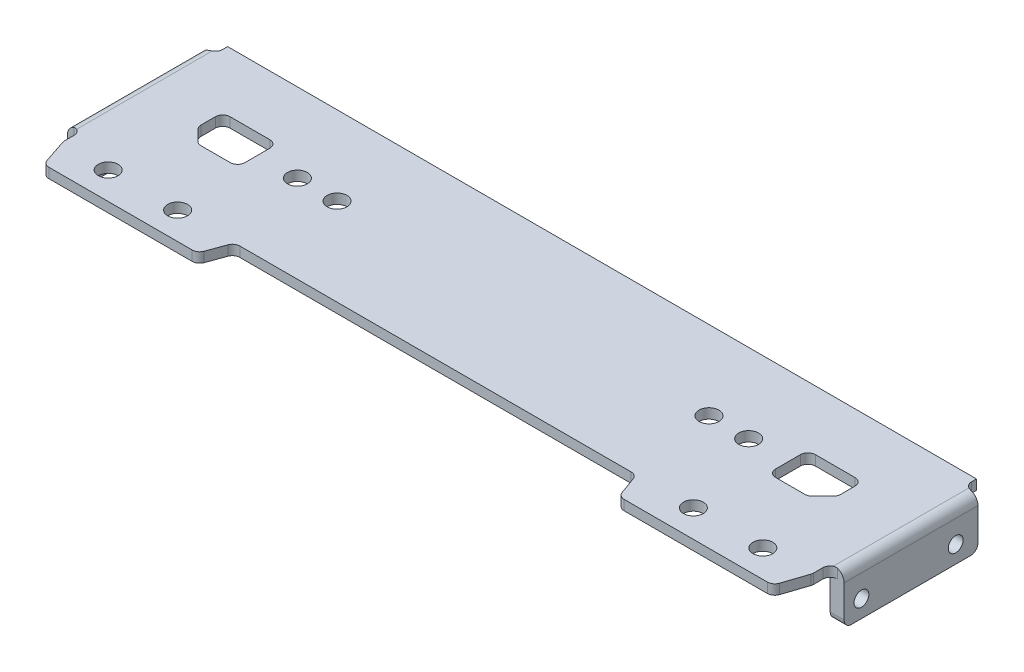
SolidWorks part; units mm, degrees
material "1060 Alloy"
ref_plane "Front Plane" through (0, 0, 0) normal (0, 0, 1) x (1, 0, 0)
ref_plane "Top Plane" through (0, 0, 0) normal (0, 1, 0) x (1, 0, 0)
ref_plane "Right Plane" through (0, 0, 0) normal (1, 0, 0) x (0, 0, -1)
sketch "Sketch1" plane through (0, 0, 0) normal (0, 1, 0) x (1, 0, 0)
  line L0 (0, 6) -> (2, 0)
  line L1 (2, 0) -> (33, 0)
  line L2 (0, 6) -> (0, 39.095)
  line L3 (0, 39.095) -> (101, 39.095)
  line L4 (101, 6) -> (101, 39.095)
  line L5 (33, 0) -> (35, 5.5)
  line L6 (50.5, 90.357) -> (50.5, -12.167) construction
  line L7 (35, 5.5) -> (66, 5.5)
  line L9 (68, 0) -> (66, 5.5)
  line L10 (99, 0) -> (68, 0)
  line L11 (101, 6) -> (99, 0)
  line L12 (11, 22.095) -> (14, 19.095)
  line L13 (11, 27.095) -> (22, 27.095)
  line L14 (11, 27.095) -> (11, 22.095)
  line L15 (14, 19.095) -> (22, 19.095)
  line L16 (22, 27.095) -> (22, 19.095)
  line L17 (90, 27.095) -> (90, 22.095)
  line L18 (90, 22.095) -> (87, 19.095)
  line L19 (87, 19.095) -> (79, 19.095)
  line L20 (79, 27.095) -> (79, 19.095)
  line L21 (90, 27.095) -> (79, 27.095)
  circle A0 centre (9.5, 5.5) radius 2
  circle A1 centre (23.5, 5.5) radius 2
  circle A2 centre (77.5, 5.5) radius 2
  circle A3 centre (91.5, 5.5) radius 2
  circle A4 centre (30, 23.1498) radius 2
  circle A5 centre (38, 23.1498) radius 2
  circle A6 centre (63, 23.1498) radius 2
  circle A7 centre (71, 23.1498) radius 2
  point P12 (50.5, 39.095)
  point P14 (50.5, 5.5)
  dimension "D1" = 4
  dimension "D2" = 9.5
  dimension "D8" = 5.5
  dimension "D9" = 14
  dimension "D16" = 4
  dimension "D17" = 8
  dimension "D18" = 8
  dimension "D3" = 6
  dimension "D4" = 2
  dimension "D5" = 31
  dimension "D6" = 5.5
  dimension "D7" = 2
  dimension "D10" = 11
  dimension "D11" = 8
  dimension "D12" = 12
  dimension "D14" = 5
  dimension "D15" = 8
extrude "Boss-Extrude1" add sketch "Sketch1" along normal blind 2
sketch "Sketch2" plane through (0, 2, 0) normal (0, 1, 0) x (1, 0, 0)
  line L0 (0, 39.095) -> (0, 6) construction
  line L1 (0, 36.595) -> (-2.8, 36.595)
  line L2 (0, 36.595) -> (0, 9.595)
  line L3 (0, 9.595) -> (-2.8, 9.595)
  line L4 (-2.8, 36.595) -> (-2.8, 9.595)
  line L5 (101, 39.095) -> (0, 39.095) construction
  line L6 (50.5, 66.5583) -> (50.5, 11.6317) construction
  line L7 (101, 9.595) -> (103.8, 9.595)
  line L8 (103.8, 36.595) -> (103.8, 9.595)
  line L9 (101, 36.595) -> (103.8, 36.595)
  line L10 (101, 36.595) -> (101, 9.595)
  point P11 (50.5, 39.095)
  dimension "D1" = 2.8
  dimension "D2" = 2.5
  dimension "D3" = 27
extrude "Boss-Extrude2" add sketch "Sketch2" against normal blind 10
sketch "Sketch3" plane through (103.8, 0, 0) normal (1, 0, 0) x (0, 0, -1)
  line L0 (9.595, -8) -> (9.595, 2) construction
  line L1 (36.595, -8) -> (36.595, 2) construction
  line L2 (9.595, -8) -> (36.595, -8) construction
  circle A0 centre (13.095, -4.5) radius 1.5
  circle A1 centre (32.095, -4.5) radius 1.5
  dimension "D1" = 3
  dimension "D2" = 3.5
  dimension "D3" = 4.5
  dimension "D4" = 3.5
extrude "Cut-Extrude1" cut sketch "Sketch3" against normal through all
fillet "Fillet1" radius 1.5 26 edges at (-1.4, -8, -9.595) (-1.4, -8, -36.595) (0, 1, -9.595) (0, 1, -6) (2, 1, 0) (0, 1, -36.595) (102.4, -8, -36.595) (101, 1, -36.595) (102.4, -8, -9.595) (101, 1, -9.595) (101, 1, -6) (99, 1, 0) (66, 1, -5.5) (68, 1, 0) (90, 1, -27.095) (79, 1, -27.095) (90, 1, -22.095) (87, 1, -19.095) (79, 1, -19.095) (35, 1, -5.5) (33, 1, 0) (11, 1, -27.095) (11, 1, -22.095) (14, 1, -19.095) (22, 1, -19.095) (22, 1, -27.095)
fillet "Fillet2" radius 2 2 edges at (-2.8, 2, -23.095) (103.8, 2, -23.095)
ref_plane "Plane1" through (50.5, 0, 0) normal (1, 0, 0) x (0, 0, -1)
sketch "Sketch4" plane through (50.5, 0, 0) normal (1, 0, 0) x (0, 0, -1)
  line L1 (-66.5909, 35.2318) -> (52.1898, 35.2318)
  line L2 (-66.5909, 35.2318) -> (-66.5909, -18.6708)
  line L3 (-66.5909, -18.6708) -> (52.1898, -18.6708)
  line L4 (52.1898, 35.2318) -> (52.1898, -18.6708)
  line L5 (-66.5909, 35.2318) -> (52.1898, -18.6708) construction
  line L6 (-66.5909, -18.6708) -> (52.1898, 35.2318) construction
  point P0 (-7.2005, 8.2805)
extrude "Cut-Extrude2" cut sketch "Sketch4" along normal blind 171
sketch "Sketch5" plane through (50.5, 0, 0) normal (1, 0, 0) x (0, 0, -1)
  line L4 (39.095, 0) -> (39.095, 2)
  line L5 (39.095, 2) -> (5.5, 2)
  line L6 (5.5, 2) -> (5.5, 0)
  line L7 (5.5, 0) -> (39.095, 0)
  line L8 (39.095, 0) -> (39.095, 2)
  line L9 (39.095, 2) -> (5.5, 2)
  line L10 (5.5, 2) -> (5.5, 0)
  line L11 (5.5, 0) -> (39.095, 0)
  dimension "D1" = 0
extrude "Boss-Extrude3" add sketch "Sketch5" along normal blind 25
mirror "Mirror1" about plane through (75.5, 0, 0) normal (1, 0, 0) of bodies 105
